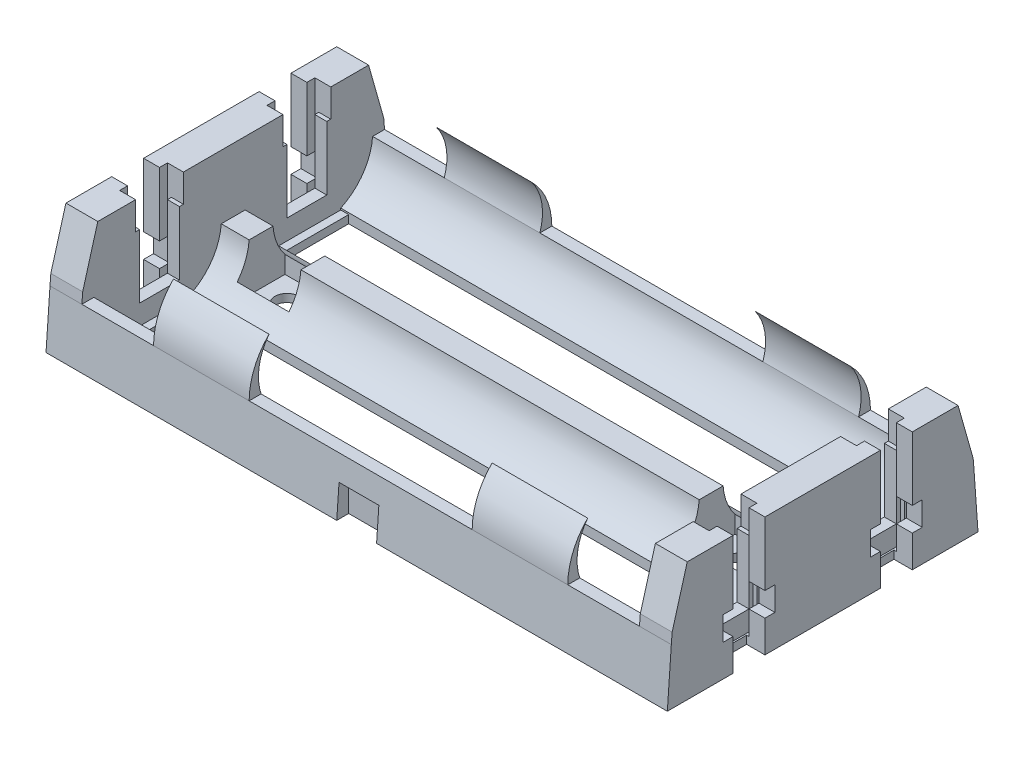
SolidWorks part; units mm, degrees
ref_plane "Front Plane" through (0, 0, 0) normal (0, 0, 1) x (1, 0, 0)
ref_plane "Top Plane" through (0, 0, 0) normal (0, 1, 0) x (1, 0, 0)
ref_plane "Right Plane" through (0, 0, 0) normal (1, 0, 0) x (0, 0, -1)
sketch "Sketch1" plane through (0, 0, 0) normal (0, 1, 0) x (1, 0, 0)
  line L0 (0, 19.5) -> (0, -19.5) construction
  line L1 (-39, 0) -> (39, 0) construction
  line L2 (-39, 19.5) -> (-39, -19.5)
  line L3 (-39, -19.5) -> (39, -19.5)
  line L4 (39, -19.5) -> (39, 19.5)
  line L5 (39, 19.5) -> (-39, 19.5)
  point P4 (0, 0)
  point P8 (0, 0)
  dimension "D1" = 39
  dimension "D2" = 78
extrude "Boss-Extrude1" add sketch "Sketch1" along normal blind 7
sketch "Sketch2" plane through (39, 0, 0) normal (1, 0, 0) x (0, 0, -1)
  line L0 (-19, 7) -> (19, 7) construction
  line L1 (-19.5, 7) -> (19.5, 7) construction
  line L3 (19, 7) -> (19.5, 0)
  line L4 (19.5, 0) -> (19.5, 7)
  line L5 (19.5, 7) -> (19, 7)
  line L6 (-19, 7) -> (-19.5, 0)
  line L7 (-19.5, 0) -> (-19.5, 7)
  line L8 (-19.5, 7) -> (-19, 7)
  point P5 (0, 7)
  dimension "D1" = 38
  dimension "D2" = 19.5
extrude "Cut-Extrude1" cut sketch "Sketch2" against normal through all
sketch "Sketch3" plane through (0, 7, 0) normal (0, 1, 0) x (1, 0, 0)
  line L0 (-35, -9.5) -> (35, -9.5) construction
  line L1 (0, -5.5) -> (0, -13.5) construction
  line L2 (-35, -5.5) -> (-35, -13.5)
  line L3 (-35, -13.5) -> (35, -13.5)
  line L4 (35, -13.5) -> (35, -5.5)
  line L5 (35, -5.5) -> (-35, -5.5)
  line L7 (-39, -19.5) -> (53.8139, -19.5) construction
  line L8 (-35, 0) -> (36.5903, 0) construction
  line L10 (35, 13.5) -> (35, 5.5)
  line L11 (-35, 13.5) -> (35, 13.5)
  line L12 (-35, 5.5) -> (-35, 13.5)
  line L13 (35, 5.5) -> (-35, 5.5)
  point P8 (0, -9.5)
  dimension "D1" = 70
  dimension "D2" = 8
  dimension "D3" = 6
extrude "Cut-Extrude2" cut sketch "Sketch3" against normal blind 6
ref_plane "Plane1" through (35, 0, 0) normal (1, 0, 0) x (0, 0, -1)
sketch "Sketch4" plane through (35, 0, 0) normal (1, 0, 0) x (0, 0, -1)
  line L0 (-19, 7) -> (19, 7) construction
  line L1 (-19.5, 0) -> (19.5, 0) construction
  line L2 (-13.5905, 3.5) -> (-4.4095, 3.5) construction
  line L3 (16.25, 8.4027) -> (16.25, -1.4027) construction
  line L4 (13, 1) -> (13, 7)
  line L5 (13, 7) -> (17.5, 7)
  arc A0 (17.5, 7) -> (13, 1) centre (10.5909, 7.4943) cw
  point P0 (17.5, 7)
  point P1 (13, 1)
  point P10 (-9, 3.5)
  point P13 (16.25, 3.5)
  dimension "D1" = 1.5
  dimension "D2" = 1
  dimension "D3" = 3.5
  dimension "D4" = 6.5
  dimension "D5" = 3.25
  dimension "D6" = 10.5
extrude "Cut-Extrude3" cut sketch "Sketch4" against normal blind 70
mirror "Mirror1" about plane through (0, 0, 0) normal (0, 0, 1) of "Cut-Extrude3"
ref_plane "Plane3" through (0, 0, -9.5) normal (0, 0, 1) x (1, 0, 0)
mirror "Mirror8" about plane through (0, 0, -9.5) normal (0, 0, 1) of "Cut-Extrude3"
ref_plane "Plane4" through (0, 0, 9.5) normal (0, 0, 1) x (1, 0, 0)
mirror "Mirror9" about plane through (0, 0, 9.5) normal (0, 0, 1) of "Mirror1"
sketch "Sketch5" plane through (0, 1, 0) normal (0, 1, 0) x (1, 0, 0)
  line L12 (-34, 5.5) -> (34, 5.5)
  line L14 (34, 13.5) -> (-34, 13.5)
  line L16 (-34, 13.5) -> (-34, 5.5)
  line L17 (34, 13.5) -> (34, 5.5)
  line L18 (-35, 17.5) -> (-35, 1.5) construction
  line L19 (35, 1.5) -> (35, 17.5) construction
  line L20 (-3.85, 0) -> (3.85, 0) construction
  line L21 (-34, -13.5) -> (-34, -5.5)
  line L22 (34, -13.5) -> (-34, -13.5)
  line L23 (34, -13.5) -> (34, -5.5)
  line L24 (-34, -5.5) -> (34, -5.5)
  dimension "D1" = 1
  dimension "D2" = 1
extrude "Cut-Extrude4" cut sketch "Sketch5" against normal through all
ref_plane "Plane2" through (26, 0, 0) normal (1, 0, 0) x (0, 0, -1)
sketch "Sketch6" plane through (26, 0, 0) normal (1, 0, 0) x (0, 0, -1)
  line L0 (-19, 7) -> (-17.5, 7)
  line L1 (-19, 7) -> (19, 7) construction
  arc A0 (-16.5, 13) -> (-19, 7) centre (-10.4706, 6.9669) ccw
  arc A1 (-16.5, 13) -> (-17.5, 7) centre (-11.2973, 9.0495) ccw
  point P5 (-16.5, 13)
  dimension "D1" = 1.5
  dimension "D2" = 6
  dimension "D3" = 2.5
extrude "Boss-Extrude2" add sketch "Sketch6" against normal blind 12
mirror "Mirror2" about plane through (0, 0, 0) normal (1, 0, 0) of "Boss-Extrude2"
mirror "Mirror3" about plane through (0, 0, 0) normal (0, 0, 1) of "Mirror2", "Boss-Extrude2"
sketch "Sketch8" plane through (39, 0, 0) normal (1, 0, 0) x (0, 0, -1)
  line L0 (-17, 15) -> (17, 15)
  line L1 (-17, 15) -> (-18.8946, 8.3043)
  line L2 (-18.8946, 8.3043) -> (-19, 7)
  line L3 (-19, 7) -> (19, 7)
  line L4 (19, 7) -> (18.8946, 8.3043)
  line L5 (18.8946, 8.3043) -> (17, 15)
  arc A0 (-16.5, 13) -> (-19, 7) centre (-10.4706, 6.9669) ccw construction
  arc A1 (19, 7) -> (16.5, 13) centre (10.4706, 6.9669) ccw construction
  point P3 (0, 15)
  dimension "D1" = 34
  dimension "D2" = 0
  dimension "D3" = 1.3043
  dimension "D4" = 8
  dimension "D5" = 1.3043
extrude "Boss-Extrude3" add sketch "Sketch8" against normal blind 4
mirror "Mirror4" about plane through (0, 0, 0) normal (1, 0, 0) of "Boss-Extrude3"
sketch "Sketch9" plane through (39, 0, 0) normal (1, 0, 0) x (0, 0, -1)
  line L0 (-12.9354, 5.5) -> (12.9354, 5.5) construction
  line L1 (-19.5, 0) -> (19.5, 0) construction
  line L2 (6, 7) -> (12.5, 7)
  line L3 (6, 7) -> (6, 4)
  line L4 (6, 4) -> (12.5, 4)
  line L5 (12.5, 4) -> (12.5, 7)
  line L6 (0, 15.8035) -> (0, -2.4722) construction
  line L7 (-6, 4) -> (-12.5, 4)
  line L8 (-6, 7) -> (-6, 4)
  line L9 (-6, 7) -> (-12.5, 7)
  line L10 (-12.5, 4) -> (-12.5, 7)
  dimension "D1" = 5.5
  dimension "D2" = 6.5
  dimension "D3" = 1.5
  dimension "D4" = 3
  dimension "D5" = 7
extrude "Cut-Extrude5" cut sketch "Sketch9" against normal blind 2
mirror "Mirror5" about plane through (0, 0, 0) normal (1, 0, 0) of "Cut-Extrude5"
sketch "Sketch11" plane through (35, 0, 0) normal (-1, 0, 0) x (0, 0, 1)
  line L1 (-17, 15) -> (17, 15) construction
  line L3 (6.75, 3.5) -> (11.75, 3.5)
  line L10 (9.25, 9.9235) -> (9.25, 0.4678) construction
  line L11 (6.75, 3.5) -> (6.75, 11.5)
  line L12 (6.75, 11.5) -> (6.25, 11.5)
  line L13 (6.25, 11.5) -> (6.25, 15)
  line L14 (6.25, 15) -> (12.25, 15)
  line L15 (12.25, 15) -> (12.25, 11.5)
  line L16 (12.25, 11.5) -> (11.75, 11.5)
  line L17 (11.75, 11.5) -> (11.75, 3.5)
  line L18 (0, 11.9457) -> (0, -3.549) construction
  line L19 (-6.75, 11.5) -> (-6.25, 11.5)
  line L20 (-6.75, 3.5) -> (-6.75, 11.5)
  line L21 (-6.75, 3.5) -> (-11.75, 3.5)
  line L22 (-11.75, 11.5) -> (-11.75, 3.5)
  line L23 (-12.25, 11.5) -> (-11.75, 11.5)
  line L24 (-12.25, 15) -> (-12.25, 11.5)
  line L25 (-6.25, 11.5) -> (-6.25, 15)
  line L26 (-6.25, 15) -> (-12.25, 15)
  point P12 (9.25, 3.5)
  dimension "D1" = 3.5
  dimension "D2" = 8
  dimension "D5" = 10.25
  dimension "D6" = 5
  dimension "D7" = 0.5
  dimension "D8" = 0.5
extrude "Cut-Extrude6" cut sketch "Sketch11" against normal blind 2
sketch "Sketch12" plane through (0, 11.5, 0) normal (0, 1, 0) x (1, 0, 0)
  line L6 (37, 6.25) -> (36.5, 6.25)
  line L7 (37, 6.25) -> (35, 6.25) construction
  line L8 (36.5, 6.25) -> (36.5, 12.25)
  line L9 (37, 12.25) -> (35, 12.25) construction
  line L10 (36.5, 12.25) -> (37, 12.25)
  line L11 (37, 12.25) -> (37, 6.25)
  line L12 (0, 0) -> (49.808, 0) construction
  line L13 (37, -6.25) -> (36.5, -6.25)
  line L14 (36.5, -12.25) -> (37, -12.25)
  line L15 (37, -12.25) -> (37, -6.25)
  line L16 (36.5, -6.25) -> (36.5, -12.25)
extrude "Cut-Extrude11" cut sketch "Sketch12" against normal blind 10.5
sketch "Sketch13" plane through (39, 0, 0) normal (1, 0, 0) x (0, 0, -1)
  line L0 (7.2491, 15) -> (11.2509, 15)
  line L1 (17, 15) -> (-17, 15) construction
  line L2 (11.2509, 15) -> (11.2509, 0)
  line L3 (-19.5, 0) -> (19.5, 0) construction
  line L4 (11.2509, 0) -> (7.2491, 0)
  line L5 (7.2491, 0) -> (7.2491, 15)
  line L6 (12.5, 7) -> (6, 7) construction
  line L7 (-6, 7) -> (-12.5, 7) construction
  line L8 (0, 16.3995) -> (0, -2.2736) construction
  line L9 (-11.2509, 0) -> (-7.2491, 0)
  line L10 (-11.2509, 15) -> (-11.2509, 0)
  line L11 (-7.2491, 15) -> (-11.2509, 15)
  line L12 (-7.2491, 0) -> (-7.2491, 15)
  point P0 (9.25, 7)
  point P10 (-9.25, 7)
  point P17 (9.25, 15)
  dimension "D1" = 4.0019
extrude "Cut-Extrude9" cut sketch "Sketch13" against normal blind 2.3
mirror "Mirror10" about plane through (0, 0, 0) normal (1, 0, 0) of "Cut-Extrude6", "Cut-Extrude11", "Cut-Extrude9"
sketch "Sketch14" plane through (0, 0, 0) normal (0, -1, 0) x (1, 0, 0)
  line L0 (-2.5, 19.5) -> (2.5, 19.5)
  line L6 (-39, 19.5) -> (39, 19.5) construction
  line L7 (2.5, 19.5) -> (2.5, 18)
  line L8 (2.5, 18) -> (-2.5, 18)
  line L9 (-2.5, 18) -> (-2.5, 19.5)
  point P6 (0, 19.5)
  dimension "D1" = 5
  dimension "D2" = 1.5
extrude "Cut-Extrude10" cut sketch "Sketch14" against normal blind 4
mirror "Mirror7" about plane through (0, 0, 0) normal (0, 0, 1) of "Cut-Extrude10"
sketch "Sketch15" plane through (0, 7, 0) normal (0, 1, 0) x (1, 0, 0)
  line L0 (-45.0943, 0) -> (43.0277, 0) construction
  line L1 (0, 24.7191) -> (0, -23.756) construction
  line L2 (-35, -1.5) -> (-35, 1.5) construction
  line L3 (-31.5, 3) -> (-25, 3)
  line L4 (-31.5, 3) -> (-31.5, -3)
  line L5 (-31.5, -3) -> (-25, -3)
  line L6 (-25, 3) -> (-25, -3)
  line L7 (-31.5, 3) -> (-25, -3) construction
  line L8 (-31.5, -3) -> (-25, 3) construction
  line L10 (31.5, -3) -> (25, -3)
  line L11 (25, 3) -> (25, -3)
  line L12 (31.5, 3) -> (25, 3)
  line L13 (31.5, 3) -> (31.5, -3)
  point P5 (-28.25, 0)
  point P12 (-28.25, -3)
  dimension "D1" = 3.5
  dimension "D2" = 6
  dimension "D3" = 6.5
extrude "Cut-Extrude12" cut sketch "Sketch15" against normal blind 6
sketch "Sketch16" plane through (0, 1, 0) normal (0, 1, 0) x (1, 0, 0)
  line L0 (0, 11.5217) -> (0, -11.2038) construction
  circle A0 centre (-28.25, 0) radius 1.5
  circle A1 centre (28.25, 0) radius 1.5
  dimension "D1" = 3
extrude "Cut-Extrude13" cut sketch "Sketch16" against normal up to next
